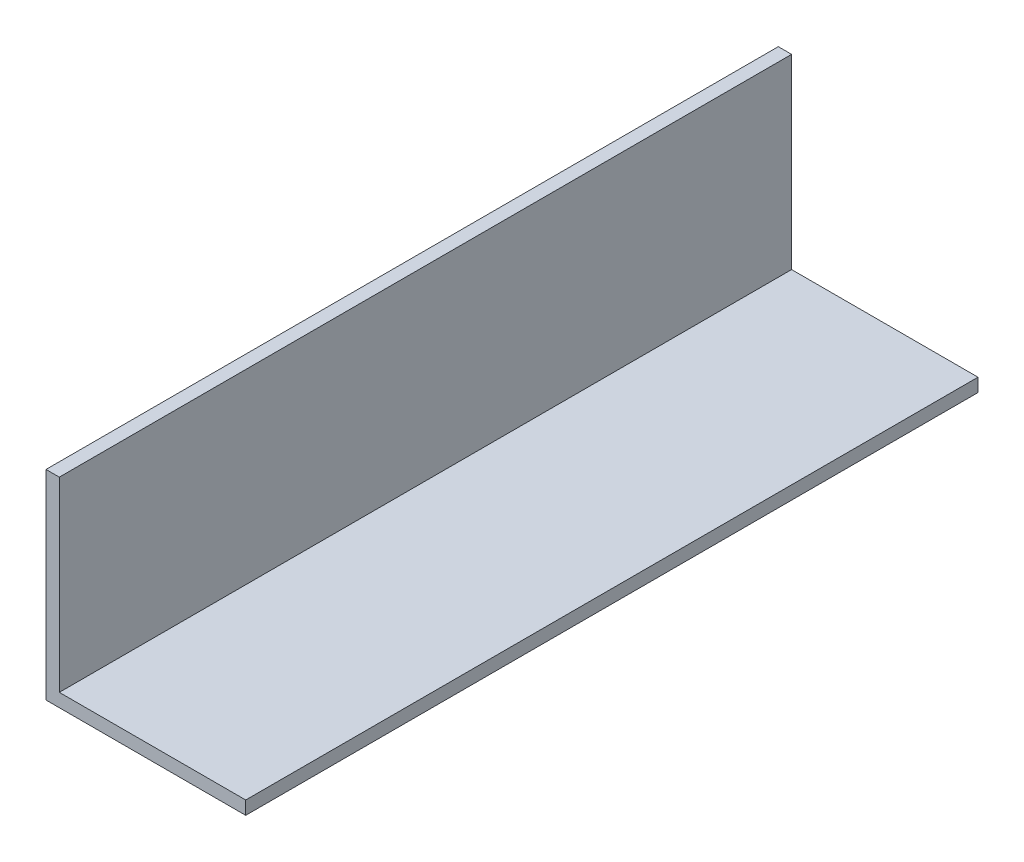
SolidWorks part; units mm, degrees
ref_plane "Front" through (0, 0, 0) normal (0, 0, 1) x (1, 0, 0)
ref_plane "Top" through (0, 0, 0) normal (0, 1, 0) x (1, 0, 0)
ref_plane "Right" through (0, 0, 0) normal (1, 0, 0) x (0, 0, -1)
sketch "Esquisse1" plane through (0, 0, 0) normal (0, 0, 1) x (1, 0, 0)
  line L0 (0, 0) -> (0, 30)
  line L1 (0, 30) -> (2, 30)
  line L2 (2, 30) -> (2, 2)
  line L3 (2, 2) -> (30, 2)
  line L4 (30, 2) -> (30, 0)
  line L5 (30, 0) -> (0, 0)
  dimension "D1" = 2
  dimension "D2" = 2
  dimension "D3" = 30
extrude "Boss.-Extru.1" add sketch "Esquisse1" along normal blind 110
